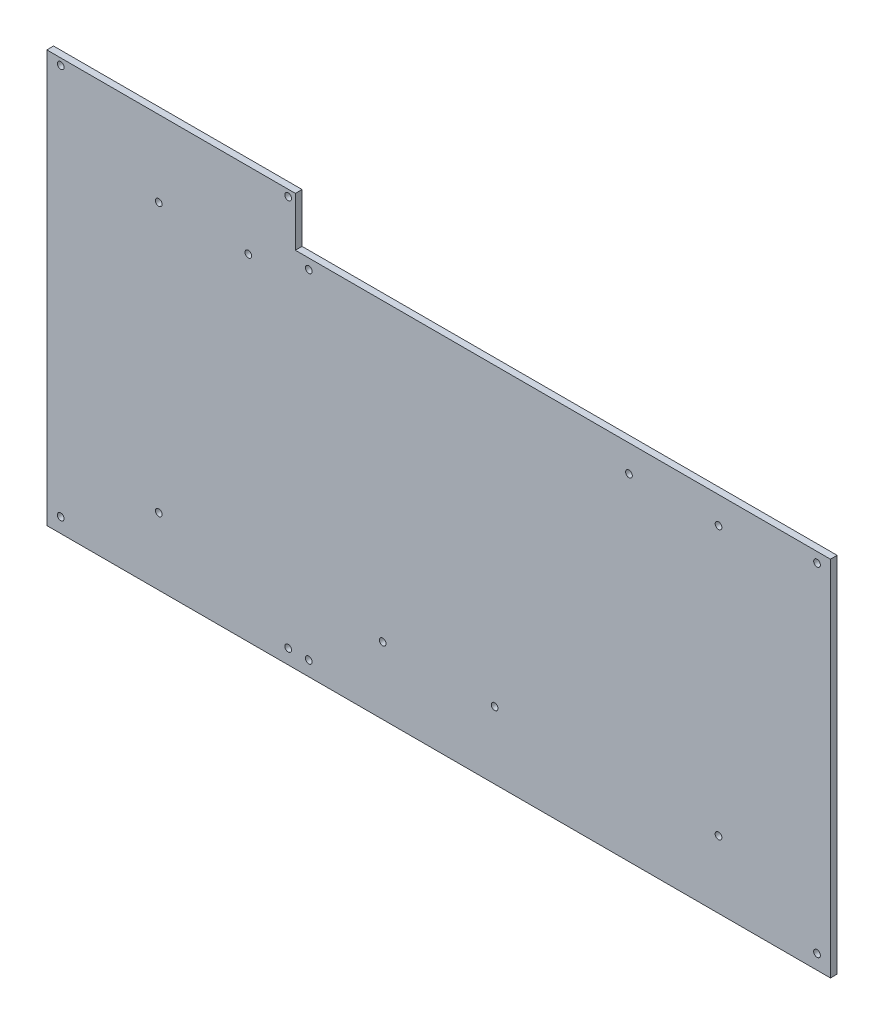
SolidWorks part; units mm, degrees
material "아크릴(내충격성)"
ref_plane "정면" through (0, 0, 0) normal (0, 0, 1) x (1, 0, 0)
ref_plane "윗면" through (0, 0, 0) normal (0, 1, 0) x (1, 0, 0)
ref_plane "우측면" through (0, 0, 0) normal (1, 0, 0) x (0, 0, -1)
sketch "스케치1" plane through (0, 0, 0) normal (0, 0, 1) x (1, 0, 0)
  line L1 (-47.2249, 90.9645) -> (191.7751, 90.9645)
  line L2 (-158.2249, 90.9645) -> (-158.2249, -71.0355)
  line L3 (-158.2249, -71.0355) -> (191.7751, -71.0355)
  line L4 (191.7751, 90.9645) -> (191.7751, -71.0355)
  line L6 (-158.2249, 90.9645) -> (-158.2249, 112.9645)
  line L7 (-158.2249, 112.9645) -> (-47.2249, 112.9645)
  line L8 (-47.2249, 90.9645) -> (-47.2249, 112.9645)
  circle A0 centre (-108.2249, 78.9645) radius 1.5
  circle A1 centre (-68.2249, 78.9645) radius 1.5
  circle A2 centre (101.7751, 78.9645) radius 1.5
  circle A3 centre (141.7751, 78.9645) radius 1.5
  circle A4 centre (141.7751, -41.0355) radius 1.5
  circle A5 centre (41.7751, -41.0355) radius 1.5
  circle A6 centre (-8.2249, -41.0355) radius 1.5
  circle A7 centre (-108.2249, -41.0355) radius 1.5
  circle A8 centre (-152.0249, 110.0645) radius 1.5
  circle A9 centre (-50.4249, 110.0645) radius 1.5
  circle A10 centre (-41.2249, 86.4645) radius 1.5
  circle A11 centre (185.7751, 86.4645) radius 1.5
  circle A12 centre (185.7751, -64.5355) radius 1.5
  circle A13 centre (-41.2249, -64.5355) radius 1.5
  circle A14 centre (-50.4249, -64.5355) radius 1.5
  circle A15 centre (-152.0249, -64.5355) radius 1.5
  dimension "D5" = 3
  dimension "D6" = 3
  dimension "D1" = 350
  dimension "D2" = 162
  dimension "D3" = 111
  dimension "D4" = 22
extrude "보스-돌출1" add sketch "스케치1" along normal blind 3
